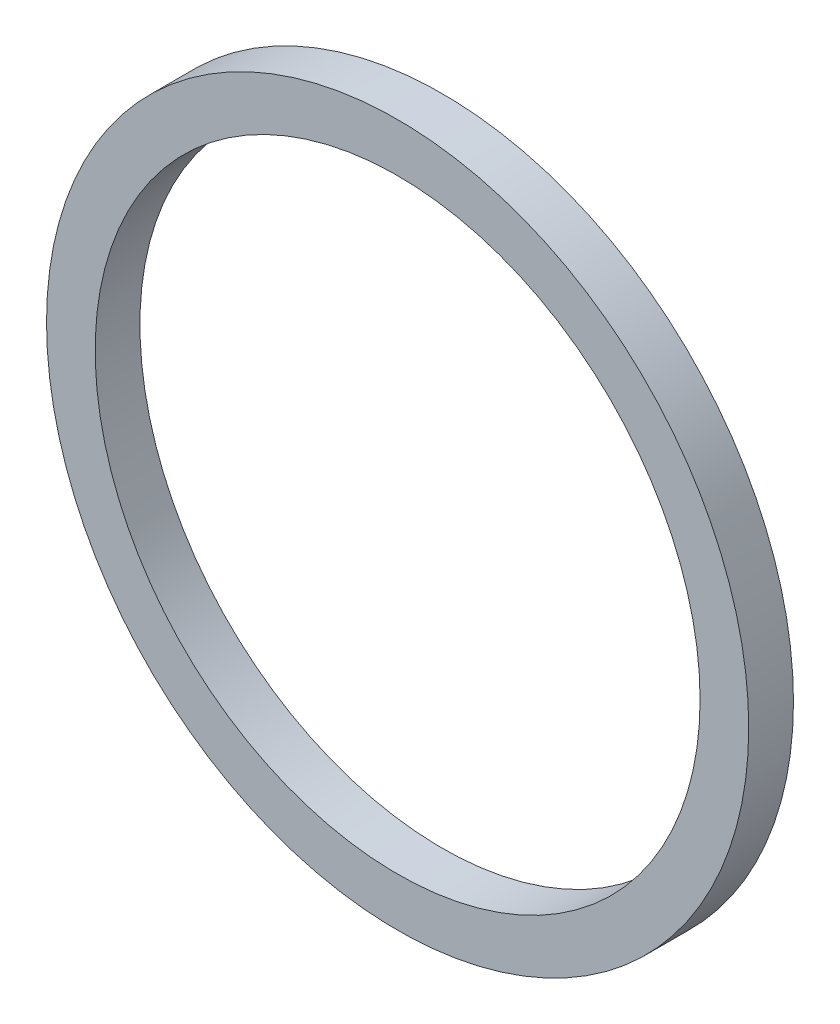
SolidWorks part; units mm, degrees
ref_plane "Front Plane" through (0, 0, 0) normal (0, 0, 1) x (1, 0, 0)
ref_plane "Top Plane" through (0, 0, 0) normal (0, 1, 0) x (1, 0, 0)
ref_plane "Right Plane" through (0, 0, 0) normal (1, 0, 0) x (0, 0, -1)
sketch "Sketch1" plane through (0, 0, 0) normal (0, 0, 1) x (1, 0, 0)
  circle A0 centre (0, 0) radius 39.4875
  circle A1 centre (0, 0) radius 45.8375
  dimension "D1" = 78.9749
  dimension "D2" = 6.35
extrude "Boss-Extrude1" add sketch "Sketch1" along normal blind 5.842
